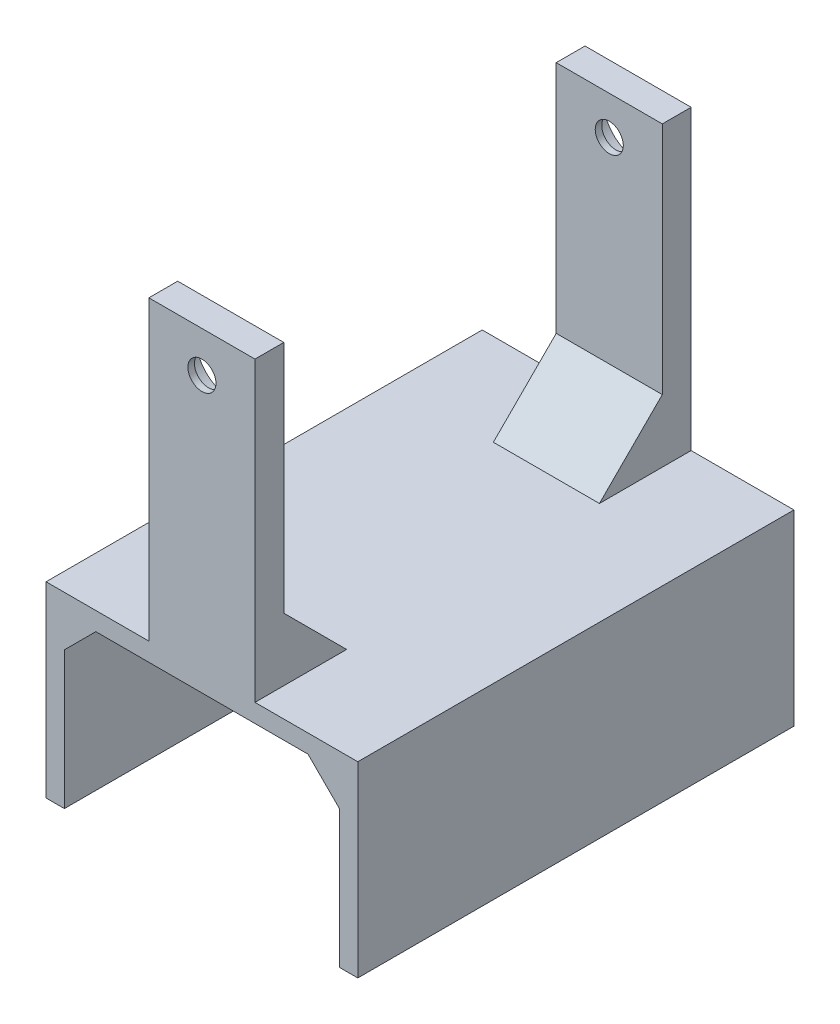
SolidWorks part; units mm, degrees
ref_plane "Plano frontal" through (0, 0, 0) normal (0, 0, 1) x (1, 0, 0)
ref_plane "Plano superior" through (0, 0, 0) normal (0, 1, 0) x (1, 0, 0)
ref_plane "Plano direito" through (0, 0, 0) normal (1, 0, 0) x (0, 0, -1)
sketch "Esboço1" plane through (0, 0, 0) normal (0, 0, 1) x (1, 0, 0)
  line L1 (49.98, -30.03) -> (-49.98, -30.03)
  line L2 (49.98, -30.03) -> (49.98, 30.03)
  line L3 (49.98, 30.03) -> (-49.98, 30.03)
  line L4 (-49.98, -30.03) -> (-49.98, 30.03)
  line L5 (49.98, -30.03) -> (-49.98, 30.03) construction
  line L6 (49.98, 30.03) -> (-49.98, -30.03) construction
  line L7 (-44.1, 24.15) -> (44.1, 24.15)
  line L8 (-44.1, 24.15) -> (-44.1, -30.03)
  line L9 (-44.1, -30.03) -> (44.1, -30.03)
  line L10 (44.1, 24.15) -> (44.1, -30.03)
  point P0 (0, 0)
  dimension "D1" = 99.96
  dimension "D2" = 60.06
  dimension "D3" = 5.88
  dimension "D4" = 5.88
  dimension "D5" = 5.88
extrude "Ressalto-extrusão1" add sketch "Esboço1" along normal blind 139.86 contours L7 L10 L1 L2 L3 L4 L8
sketch "Esboço2" plane through (0, 0, 139.86) normal (0, 0, 1) x (1, 0, 0)
  line L0 (-44.1, 24.15) -> (-44.1, 14.07)
  line L1 (-44.1, 24.15) -> (-44.1, -30.03) construction
  line L2 (-44.1, 14.07) -> (-34.02, 24.15)
  line L3 (-44.1, 24.15) -> (44.1, 24.15) construction
  line L4 (-34.02, 24.15) -> (-44.1, 24.15)
  line L5 (44.1, 24.15) -> (44.1, 14.07)
  line L6 (44.1, 24.15) -> (44.1, -30.03) construction
  line L7 (44.1, 14.07) -> (34.02, 24.15)
  line L8 (34.02, 24.15) -> (44.1, 24.15)
  dimension "D1" = 10.08
  dimension "D2" = 10.08
  dimension "D3" = 10.08
  dimension "D4" = 10.08
extrude "Ressalto-extrusão2" add sketch "Esboço2" against normal blind 139.86
sketch "Esboço3" plane through (0, 0, 139.86) normal (0, 0, 1) x (1, 0, 0)
  line L0 (49.98, 30.03) -> (-49.98, 30.03) construction
  line L1 (17.01, 125.37) -> (-17.01, 125.37)
  line L2 (17.01, 125.37) -> (17.01, 30.03)
  line L3 (17.01, 30.03) -> (-17.01, 30.03)
  line L4 (-17.01, 125.37) -> (-17.01, 30.03)
  line L5 (17.01, 125.37) -> (-17.01, 30.03) construction
  line L6 (17.01, 30.03) -> (-17.01, 125.37) construction
  line L9 (49.98, -30.03) -> (49.98, 30.03) construction
  point P0 (0, 77.7)
  dimension "D1" = 95.34
  dimension "D2" = 34.02
  dimension "D3" = 49.98
extrude "Ressalto-extrusão3" add sketch "Esboço3" against normal blind 9.24
sketch "Esboço4" plane through (0, 0, 139.86) normal (0, 0, 1) x (1, 0, 0)
  line L0 (17.01, 125.37) -> (-17.01, 125.37) construction
  circle A0 centre (0, 112.35) radius 4.5
  dimension "D1" = 9
  dimension "D2" = 13.02
extrude "Corte-extrusão1" cut sketch "Esboço4" against normal blind 9.24
sketch "Esboço5" [suppressed] plane through (0, 0, 139.86) normal (0, 0, 1) x (1, 0, 0)
  circle A0 centre (0, 112.35) radius 11.13
  dimension "D1" = 22.26
extrude "Corte-extrusão2" [suppressed] cut sketch "Esboço5" against normal blind 7.14
sketch "Esboço6" plane through (17.01, 0, 0) normal (1, 0, 0) x (0, 0, -1)
  line L0 (-130.62, 50.19) -> (-130.62, 30.03)
  line L1 (-130.62, 30.03) -> (-130.62, 125.37) construction
  line L2 (-130.62, 30.03) -> (-139.86, 30.03) construction
  line L3 (-130.62, 30.03) -> (-110.46, 30.03)
  line L4 (-139.86, 30.03) -> (0, 30.03) construction
  line L5 (-110.46, 30.03) -> (-130.62, 50.19)
  dimension "D1" = 20.16
  dimension "D2" = 20.16
extrude "Ressalto-extrusão4" add sketch "Esboço6" against normal blind 34.02
sketch "Esboço7" plane through (0, 0, 0) normal (0, 0, -1) x (-1, 0, 0)
  line L1 (17.01, 30.03) -> (-17.01, 30.03)
  line L2 (17.01, 30.03) -> (17.01, 125.37)
  line L3 (17.01, 125.37) -> (-17.01, 125.37)
  line L4 (-17.01, 30.03) -> (-17.01, 125.37)
extrude "Ressalto-extrusão5" add sketch "Esboço7" against normal blind 9.24 contours L4 L3 L2 L1
sketch "Esboço8" plane through (0, 0, 0) normal (0, 0, -1) x (-1, 0, 0)
  circle A0 centre (0, 113.1086) radius 4.5
  dimension "D1" = 9
extrude "Corte-extrusão3" cut sketch "Esboço8" against normal blind 9.24
sketch "Esboço9" plane through (0, 0, 0) normal (0, 0, -1) x (-1, 0, 0)
  circle A0 centre (0, 113.1086) radius 11.13
  dimension "D1" = 22.26
extrude "Corte-extrusão4" cut sketch "Esboço9" against normal blind 7.14
sketch "Esboço10" plane through (17.01, 0, 0) normal (1, 0, 0) x (0, 0, -1)
  line L0 (-9.24, 30.03) -> (-9.24, 50.19)
  line L1 (-9.24, 30.03) -> (-9.24, 125.37) construction
  line L2 (-9.24, 50.19) -> (-29.4, 30.03)
  line L3 (-139.86, 30.03) -> (0, 30.03) construction
  line L4 (-29.4, 30.03) -> (-9.24, 30.03)
  dimension "D1" = 20.16
  dimension "D2" = 20.16
extrude "Ressalto-extrusão6" add sketch "Esboço10" against normal blind 34.02
sketch "Esboço12" plane through (0, 0, 130.62) normal (0, 0, -1) x (-1, 0, 0)
  circle A0 centre (0, 112.35) radius 11.13
  dimension "D1" = 22.26
extrude "Corte-extrusão5" cut sketch "Esboço12" against normal blind 7.14
